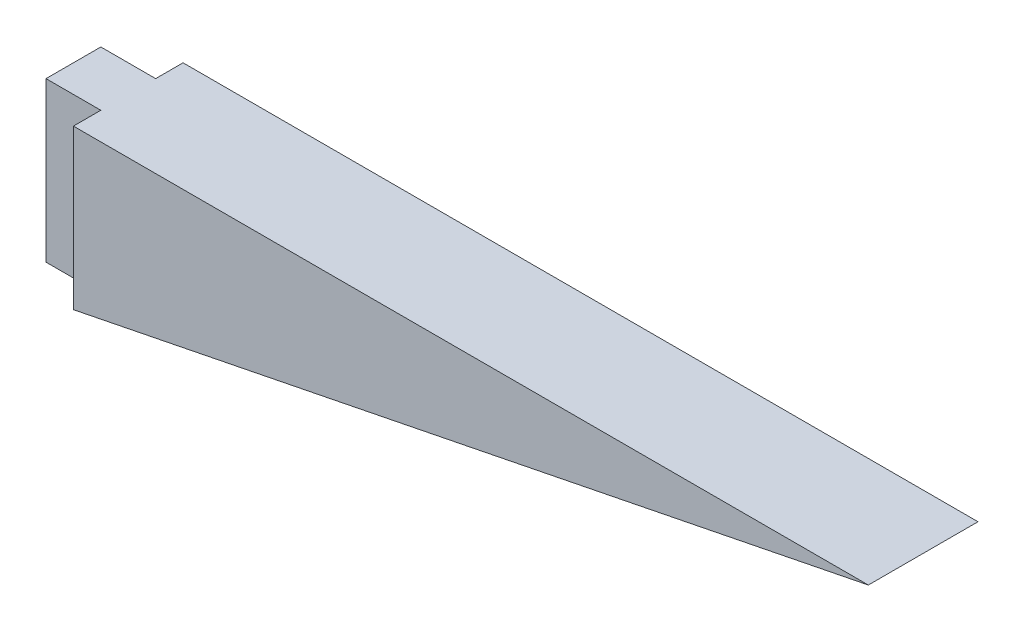
SolidWorks part; units mm, degrees
ref_plane "Front Plane" through (0, 0, 0) normal (0, 0, 1) x (1, 0, 0)
ref_plane "Top Plane" through (0, 0, 0) normal (0, 1, 0) x (1, 0, 0)
ref_plane "Right Plane" through (0, 0, 0) normal (1, 0, 0) x (0, 0, -1)
sketch "Sketch2" plane through (0, 0, 0) normal (0, 1, 0) x (1, 0, 0)
  line L1 (0, 0) -> (14.5, 0)
  line L2 (0, 0) -> (0, 2)
  line L3 (0, 2) -> (14.5, 2)
  line L4 (14.5, 0) -> (14.5, 2)
extrude "Boss-Extrude1" add sketch "Sketch2" along normal blind 3
sketch "Sketch5" plane through (0, 0, 0) normal (0, 0, 1) x (1, 0, 0)
  line L0 (14.5, 3) -> (-1.1893, -0.1379)
  line L1 (14.5, 3) -> (14.5, -0.1379)
  line L3 (14.5, -0.1379) -> (-1.1893, -0.1379)
extrude "Cut-Extrude2" cut sketch "Sketch5" against normal blind 10
sketch "Sketch6" plane through (0, 0, 0) normal (-1, 0, 0) x (0, 0, 1)
  line L0 (-2, 3) -> (0, 3) construction
  line L1 (-1.5, 3) -> (-0.5, 3)
  line L2 (-1.5, 3) -> (-1.5, 0.1)
  line L3 (-1.5, 0.1) -> (-0.5, 0.1)
  line L4 (-0.5, 3) -> (-0.5, 0.1)
  line L5 (-2, 0.1) -> (0, 0.1) construction
extrude "Boss-Extrude3" add sketch "Sketch6" along normal blind 1
